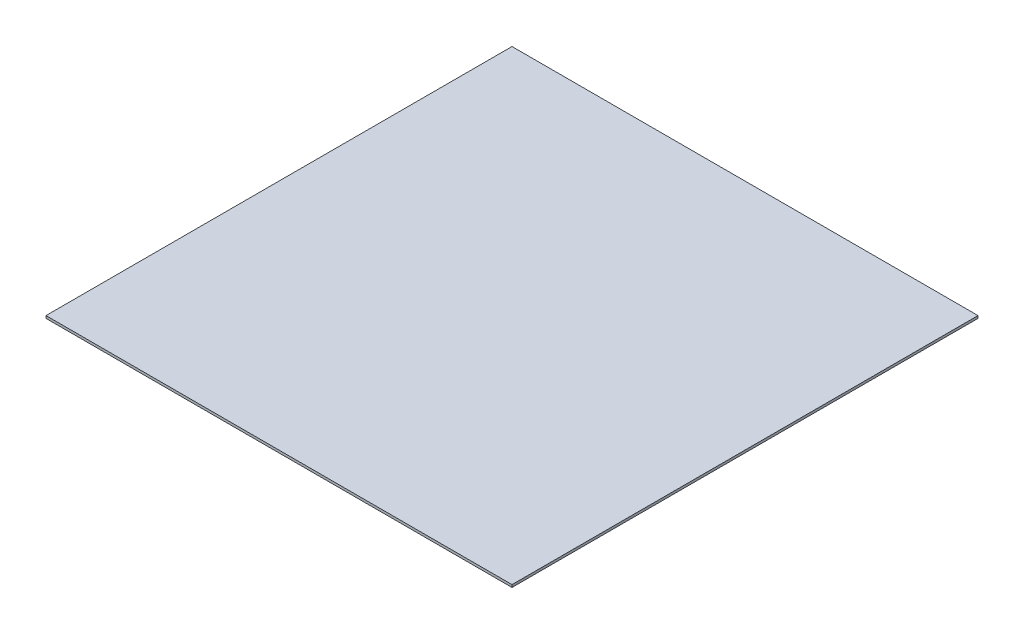
SolidWorks part; units mm, degrees
material "Silicon"
ref_plane "Front Plane" through (0, 0, 0) normal (0, 0, 1) x (1, 0, 0)
ref_plane "Top Plane" through (0, 0, 0) normal (0, 1, 0) x (1, 0, 0)
ref_plane "Right Plane" through (0, 0, 0) normal (1, 0, 0) x (0, 0, -1)
sketch "Sketch1" plane through (0, 0, 0) normal (0, 1, 0) x (1, 0, 0)
  line L1 (0, 0) -> (300, 0)
  line L2 (0, 0) -> (0, 300)
  line L3 (0, 300) -> (300, 300)
  line L4 (300, 0) -> (300, 300)
  point P5 (0, 0)
  dimension "D1" = 300
  dimension "D2" = 300
extrude "Boss-Extrude1" add sketch "Sketch1" along normal blind 1.6
